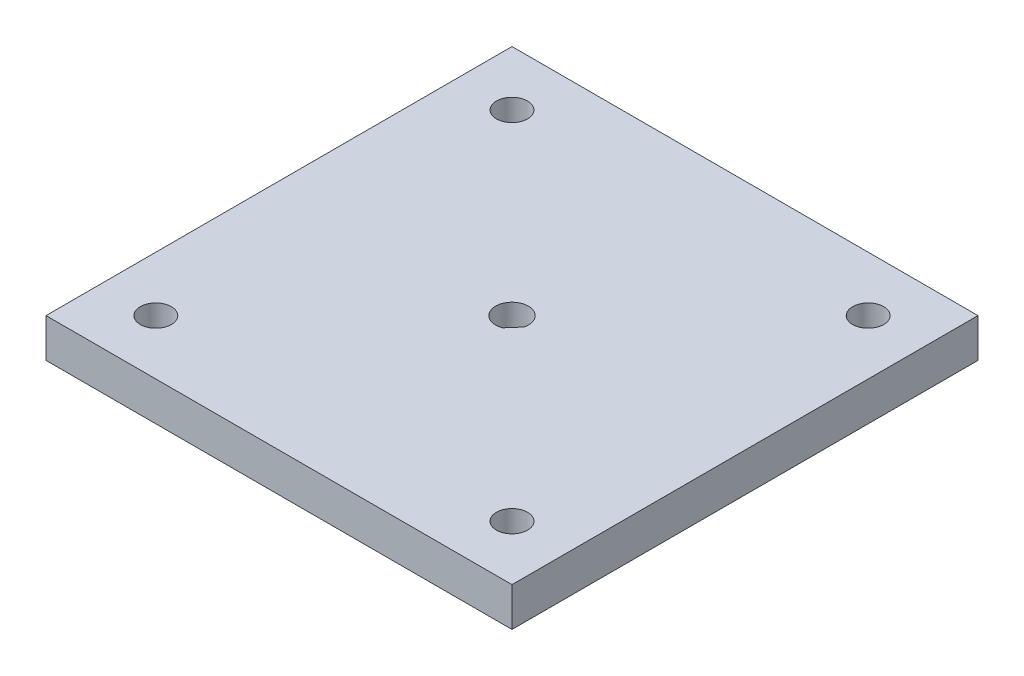
SolidWorks part; units mm, degrees
ref_plane "Front Plane" through (0, 0, 0) normal (0, 0, 1) x (1, 0, 0)
ref_plane "Top Plane" through (0, 0, 0) normal (0, 1, 0) x (1, 0, 0)
ref_plane "Right Plane" through (0, 0, 0) normal (1, 0, 0) x (0, 0, -1)
sketch "Sketch1" plane through (0, 0, 0) normal (0, 1, 0) x (1, 0, 0)
  line L0 (0.976, -2.4993) -> (2.6091, -0.6258)
  line L2 (38.1, 38.1) -> (-38.1, 38.1)
  line L3 (38.1, 38.1) -> (38.1, -38.1)
  line L4 (38.1, -38.1) -> (-38.1, -38.1)
  line L5 (-38.1, 38.1) -> (-38.1, -38.1)
  line L6 (38.1, 38.1) -> (-38.1, -38.1) construction
  line L7 (38.1, -38.1) -> (-38.1, 38.1) construction
  circle A0 centre (0, 0) radius 2.6831
  circle A1 centre (-29.1204, 29.1204) radius 2.54
  circle A2 centre (29.1204, 29.1204) radius 2.54
  circle A3 centre (29.1204, -29.1204) radius 2.54
  circle A4 centre (-29.1204, -29.1204) radius 2.54
  point P17 (0, 0)
  point P18 (0, 0)
  point P19 (0, 0)
  point P20 (0, 0)
  point P21 (-24.0678, 24.0678)
  point P22 (-29.1204, -29.1204)
  dimension "D1" = 5.3662
  dimension "D3" = 5.08
  dimension "D2" = 76.2
extrude "Boss-Extrude1" add sketch "Sketch1" along normal blind 6.35 contours L2 L5 L4 L3 A4 A3 A2 A1 A0 | L0 A0
